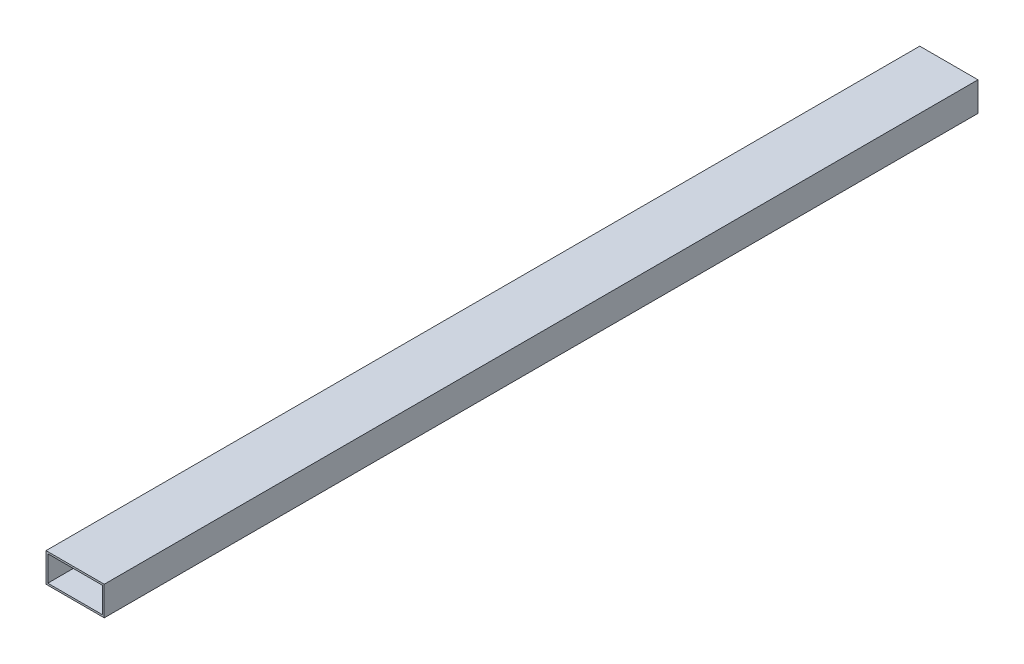
SolidWorks part; units mm, degrees
ref_plane "Front Plane" through (0, 0, 0) normal (0, 0, 1) x (1, 0, 0)
ref_plane "Top Plane" through (0, 0, 0) normal (0, 1, 0) x (1, 0, 0)
ref_plane "Right Plane" through (0, 0, 0) normal (1, 0, 0) x (0, 0, -1)
sketch "Sketch1" plane through (0, 0, 0) normal (0, 0, 1) x (1, 0, 0)
  line L1 (-46.8772, 18.6332) -> (3.9228, 18.6332)
  line L2 (-46.8772, 18.6332) -> (-46.8772, -6.7668)
  line L3 (-46.8772, -6.7668) -> (3.9228, -6.7668)
  line L4 (3.9228, 18.6332) -> (3.9228, -6.7668)
  dimension "D1" = 50.8
  dimension "D2" = 25.4
extrude "Extrude-Thin1" add sketch "Sketch1" along normal blind 762 thin
